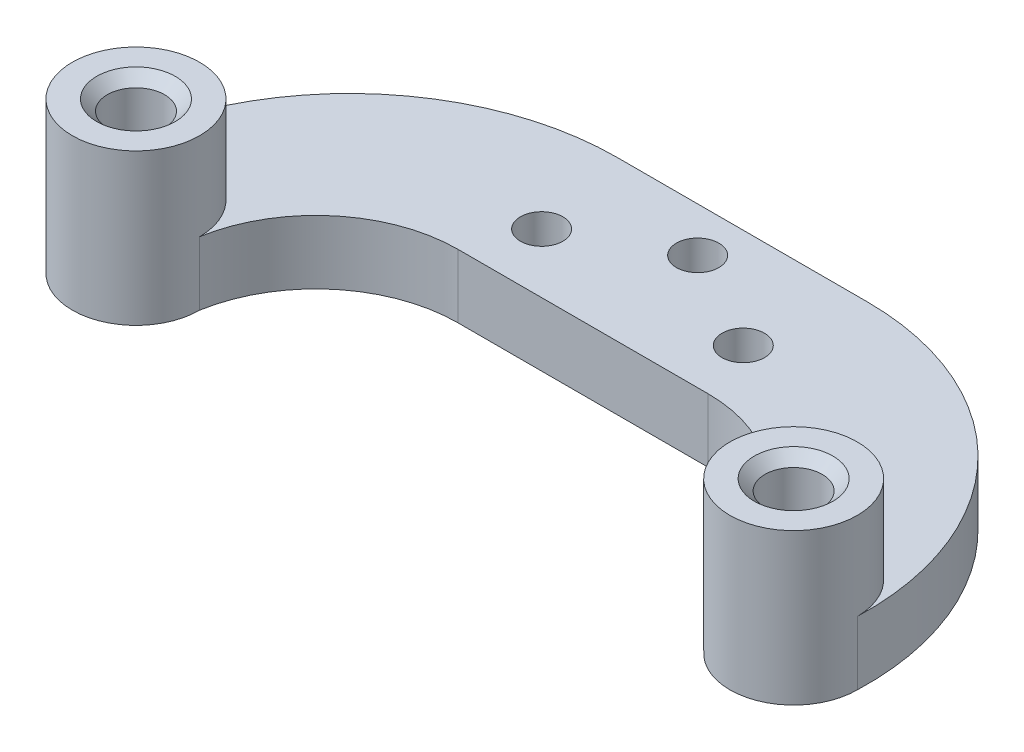
SolidWorks part; units mm, degrees
ref_plane "Front Plane" through (0, 0, 0) normal (0, 0, 1) x (1, 0, 0)
ref_plane "Top Plane" through (0, 0, 0) normal (0, 1, 0) x (1, 0, 0)
ref_plane "Right Plane" through (0, 0, 0) normal (1, 0, 0) x (0, 0, -1)
sketch "Sketch1" plane through (0, 0, 0) normal (0, 1, 0) x (1, 0, 0)
  line L0 (0, 0) -> (0, -2.1) construction
  line L1 (0, -2.1) -> (0, -4.7) construction
  line L2 (0, 0) -> (0, -17.45) construction
  line L3 (-4.75, -4.7) -> (4.75, -4.7) construction
  line L4 (0, -17.45) -> (0, -13.07)
  line L5 (-15.4928, -13.07) -> (15.4928, -13.07) construction
  line L6 (0, 0) -> (0, -7.5) construction
  line L7 (-5.8863, -7.5) -> (5.8863, -7.5)
  line L9 (-5.8863, -7.5) -> (5.8863, -7.5)
  line L10 (-5.8863, -7.5) -> (-5.8863, 0)
  line L11 (-5.8863, 0) -> (5.8863, 0)
  line L12 (5.8863, -7.5) -> (5.8863, 0)
  circle A0 centre (-15.4928, -13.07) radius 1.35
  circle A1 centre (15.4928, -13.07) radius 1.35
  circle A2 centre (-15.4928, -13.07) radius 3
  circle A3 centre (15.4928, -13.07) radius 3
  circle A4 centre (-4.75, -4.7) radius 1
  circle A5 centre (4.75, -4.7) radius 1
  circle A6 centre (0, -2.1) radius 1
  arc A7 (-5.8863, -7.5) -> (-12.4928, -13.07) centre (-5.8863, -14.203) ccw
  arc A8 (5.8863, -7.5) -> (12.4928, -13.07) centre (5.8863, -14.203) cw
  arc A9 (-5.8863, 0) -> (-18.4928, -13.07) centre (-5.8863, -12.6148) ccw
  arc A10 (5.8863, 0) -> (18.4928, -13.07) centre (5.8863, -12.6148) cw
  point P7 (0, -4.7)
  point P14 (0, -13.07)
  point P23 (0, -7.5)
  point P34 (0, 0)
  dimension "D7" = 2.7
  dimension "D8" = 2.7
  dimension "D9" = 6
  dimension "D10" = 6
  dimension "D11" = 2
  dimension "D12" = 2
  dimension "D13" = 2
  dimension "D1" = 2.1
  dimension "D2" = 2.6
  dimension "D3" = 17.45
  dimension "D4" = 9.5
  dimension "D5" = 4.38
  dimension "D6" = 30.9856
  dimension "D15" = 7.5
extrude "Boss-Extrude1" add sketch "Sketch1" along normal blind 3 contours A10 L12 A8 A3 | L7 L12 L11 L10 A6 A5 A4 | L10 A9 A2 A7 | A2 A0 | A3 A1
ref_plane "Plane1" through (0, 0, 13.07) normal (0, 0, 1) x (1, 0, 0)
ref_axis "Axis2" through (-15.4928, 3, 13.07) along (0, -1, 0)
sketch "Sketch4" plane through (0, 0, 13.07) normal (0, 0, 1) x (1, 0, 0)
  line L0 (-18.4928, 3) -> (-16.8428, 3)
  line L1 (-16.8428, 3) -> (-16.8428, 7.12)
  line L2 (-16.8428, 7.12) -> (-18.4928, 7.12)
  line L3 (-18.4928, 7.12) -> (-18.4928, 3)
  dimension "D1" = 4.12
revolve "Revolve2" add sketch "Sketch4" angle 360 about axis through (-15.4928, 3, 13.07) along (0, -1, 0)
chamfer "Chamfer1" distance 0.5 angle 45 1 edges at (-15.4928, 7.12, 14.42)
mirror "Mirror1" about plane through (0, 0, 0) normal (1, 0, 0) of "Chamfer1", "Revolve2"
